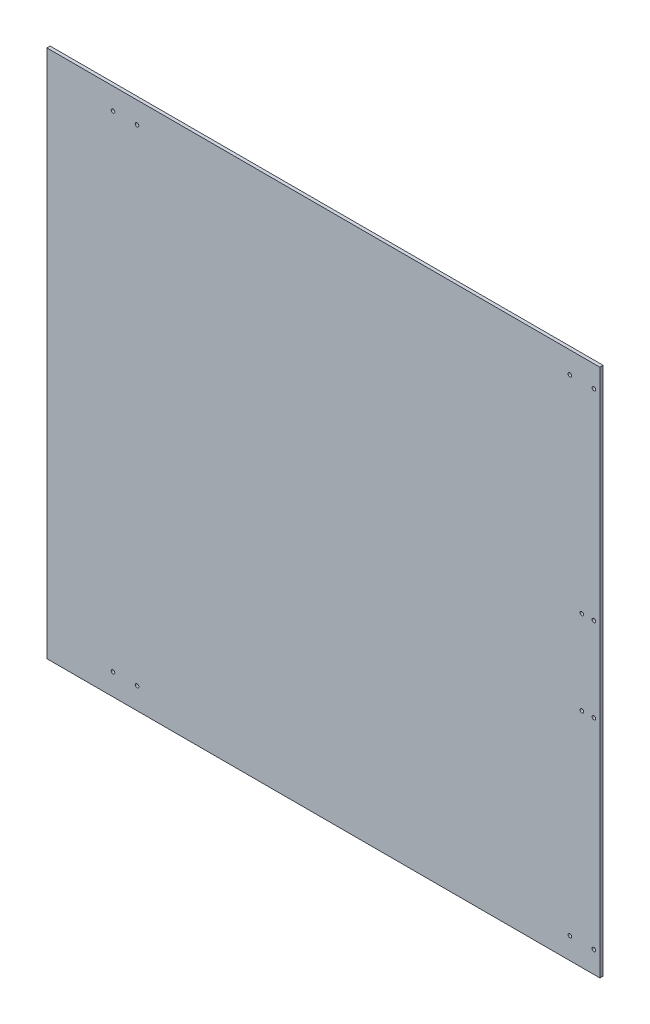
SolidWorks part; units mm, degrees
ref_plane "前视基准面" through (0, 0, 0) normal (0, 0, 1) x (1, 0, 0)
ref_plane "上视基准面" through (0, 0, 0) normal (0, 1, 0) x (1, 0, 0)
ref_plane "右视基准面" through (0, 0, 0) normal (1, 0, 0) x (0, 0, -1)
other "Configuration Table"
sketch "草图1" plane through (0, 0, 0) normal (0, 0, 1) x (1, 0, 0)
  line L1 (0, 0) -> (-460, 0)
  line L2 (0, 0) -> (0, 440)
  line L3 (0, 440) -> (-460, 440)
  line L4 (-460, 0) -> (-460, 440)
  dimension "D1" = 440
  dimension "D2" = 460
extrude "凸台-拉伸1" add sketch "草图1" along normal blind 2.7
sketch "草图2" plane through (0, 0, 2.7) normal (0, 0, 1) x (1, 0, 0)
  line L2 (0, 440) -> (0, 422) construction
  line L3 (0, 0) -> (0, 440) construction
  line L4 (0, 422) -> (-5, 422) construction
  line L5 (-5, 422) -> (-25, 422) construction
  line L6 (0, 220) -> (-173.4631, 220) construction
  line L7 (-5, 18) -> (-25, 18) construction
  line L8 (0, 18) -> (-5, 18) construction
  line L9 (0, 0) -> (0, 18) construction
  line L10 (-25, 422) -> (-385, 422) construction
  line L11 (-385, 422) -> (-405, 422) construction
  line L12 (-385, 18) -> (-405, 18) construction
  circle A4 centre (-5, 422) radius 1.5
  circle A5 centre (-25, 422) radius 1.5
  circle A6 centre (-25, 18) radius 1.5
  circle A7 centre (-5, 18) radius 1.5
  circle A8 centre (-385, 422) radius 1.5
  circle A9 centre (-405, 422) radius 1.5
  circle A10 centre (-405, 18) radius 1.5
  circle A11 centre (-385, 18) radius 1.5
  dimension "D4" = 3
  dimension "D5" = 3
  dimension "D8" = 3
  dimension "D9" = 3
  dimension "D1" = 18
  dimension "D2" = 5
  dimension "D3" = 20
  dimension "D6" = 360
  dimension "D7" = 20
extrude "切除-拉伸1" cut sketch "草图2" against normal blind 10
sketch "草图3" plane through (0, 0, 2.7) normal (0, 0, 1) x (1, 0, 0)
  line L0 (0, 440) -> (0, 255) construction
  line L1 (0, 0) -> (0, 440) construction
  line L2 (0, 255) -> (-5, 255) construction
  line L3 (-5, 255) -> (-15, 255) construction
  line L4 (0, 220) -> (-147.9326, 220) construction
  line L5 (-5, 185) -> (-15, 185) construction
  line L6 (0, 185) -> (-5, 185) construction
  circle A0 centre (-15, 255) radius 1.5
  circle A1 centre (-5, 255) radius 1.5
  circle A2 centre (-5, 185) radius 1.5
  circle A3 centre (-15, 185) radius 1.5
  dimension "D4" = 3
  dimension "D5" = 3
  dimension "D1" = 185
  dimension "D2" = 5
  dimension "D3" = 10
extrude "切除-拉伸2" cut sketch "草图3" against normal blind 10
